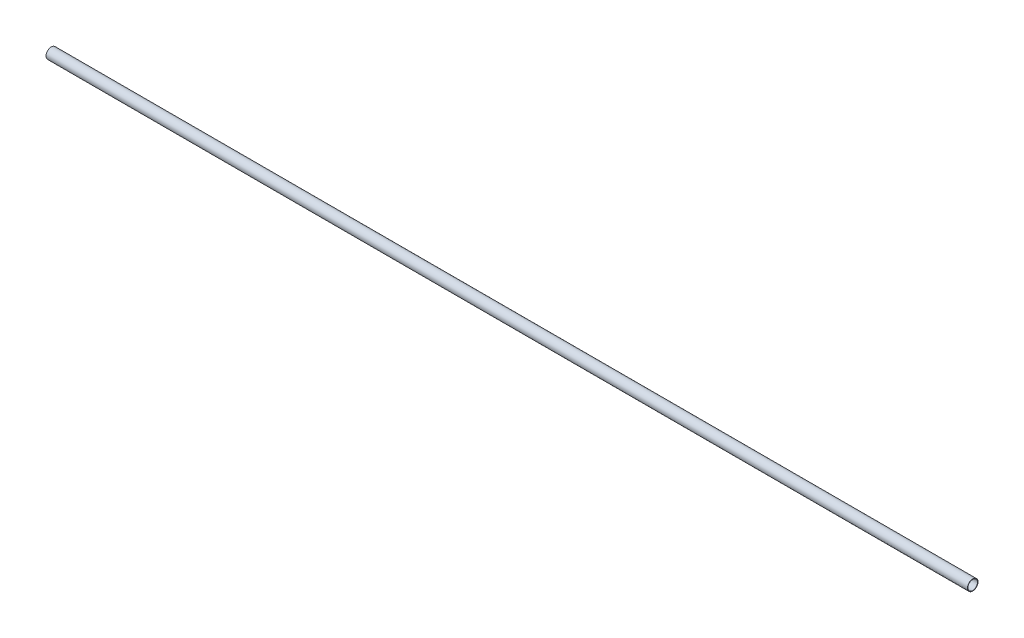
SolidWorks part; units mm, degrees
material "PF"
ref_plane "Front Plane" through (0, 0, 0) normal (0, 0, 1) x (1, 0, 0)
ref_plane "Top Plane" through (0, 0, 0) normal (0, 1, 0) x (1, 0, 0)
ref_plane "Right Plane" through (0, 0, 0) normal (1, 0, 0) x (0, 0, -1)
sketch "Sketch1" plane through (0, 0, 0) normal (1, 0, 0) x (0, 0, -1)
  circle A0 centre (0, 0) radius 6.985
  dimension "D1" = 13.97
extrude "Boss-Extrude1" add sketch "Sketch1" along normal blind 1219.2
sketch "Sketch2" plane through (0, 0, 0) normal (-1, 0, 0) x (0, 0, 1)
  circle A0 centre (0, 0) radius 6.35
  dimension "D1" = 12.7
extrude "Cut-Extrude1" cut sketch "Sketch2" against normal through all
